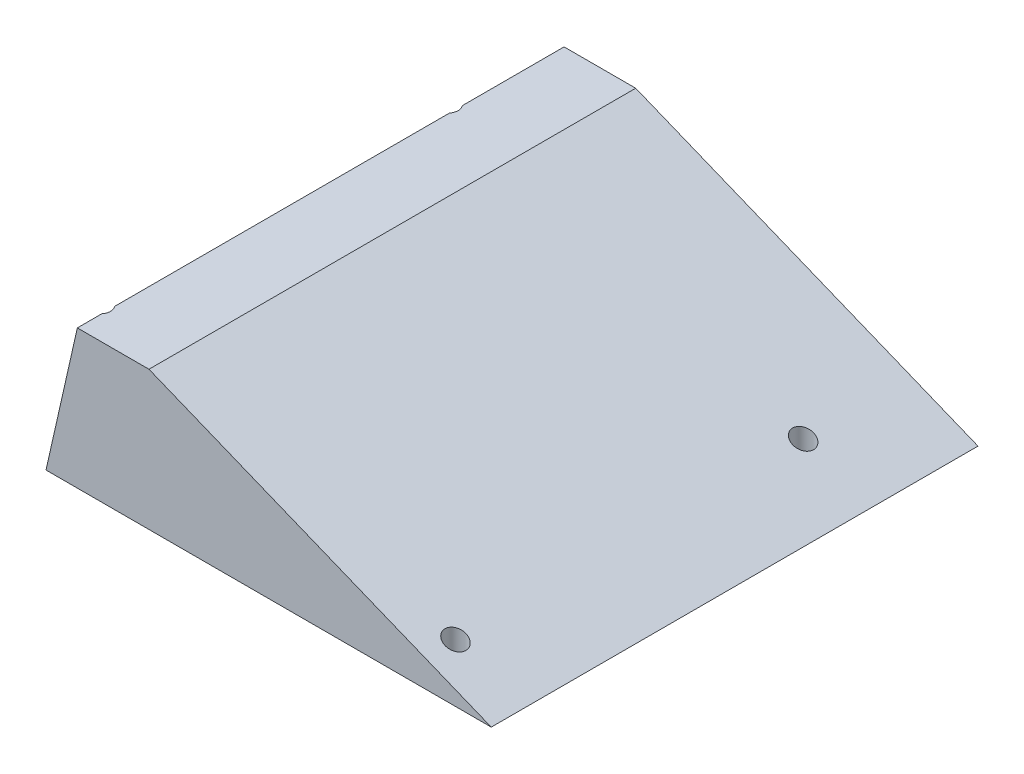
SolidWorks part; units mm, degrees
ref_plane "Front" through (0, 0, 0) normal (0, 0, 1) x (1, 0, 0)
ref_plane "Top" through (0, 0, 0) normal (0, 1, 0) x (1, 0, 0)
ref_plane "Right" through (0, 0, 0) normal (1, 0, 0) x (0, 0, -1)
sketch "草图1" plane through (0, 0, 0) normal (0, 0, 1) x (1, 0, 0)
  line L0 (5.3689, 0) -> (10.7378, 0)
  line L1 (63, 0) -> (18.6962, 17.9645)
  line L2 (18.6962, 17.9645) -> (9.4265, 17.9645)
  line L3 (13.4333, 10.8252) -> (10.7378, 0)
  line L5 (13.4333, 10.8252) -> (27.262, 10.8252)
  line L6 (27.262, 10.8252) -> (31.5, 0)
  line L7 (31.5, 0) -> (63, 0)
  line L8 (9.4265, 17.9645) -> (5.3689, 0)
extrude "凸台-拉伸1" add sketch "草图1" along normal blind 63
sketch "草图2" plane through (0, 0, 63) normal (0, 0, 1) x (1, 0, 0)
  line L0 (10.7378, 0) -> (31.5, 0)
  line L1 (31.5, 0) -> (27.262, 10.8252)
  line L2 (27.262, 10.8252) -> (13.4333, 10.8252)
  line L3 (13.4333, 10.8252) -> (10.7378, 0)
extrude "凸台-拉伸2" add sketch "草图2" against normal blind 6
sketch "草图3" plane through (0, 0, 0) normal (1, 0, 0) x (0, 0, -1)
  line L0 (0, 0) -> (0, 10)
  line L1 (0, 0) -> (0, 17.9645) construction
  line L2 (0, 10) -> (-8, 10)
  line L3 (-8, 10) -> (-8, 0)
  line L4 (-63, 0) -> (0, 0) construction
  line L5 (-8, 0) -> (0, 0)
extrude "切除-拉伸1" cut sketch "草图3" along normal blind 19
sketch "草图4" plane through (0, 0, 0) normal (0, -1, 0) x (1, 0, 0)
  circle A0 centre (8.3689, 59) radius 1.35
  circle A1 centre (54.3689, 59) radius 1.35
  circle A2 centre (54.3689, 14) radius 1.35
  circle A3 centre (8.3689, 14) radius 1.35
extrude "切除-拉伸2" cut sketch "草图4" against normal blind 27
